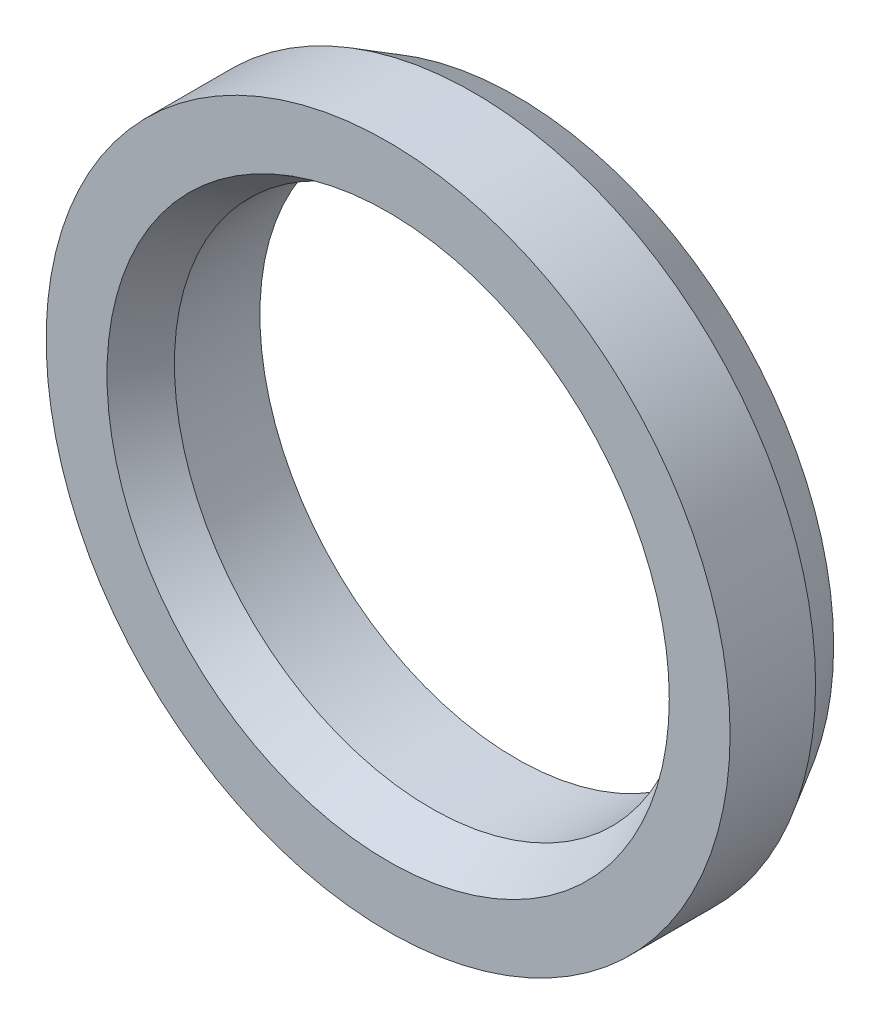
SolidWorks part; units mm, degrees
material "未指定"
ref_plane "正面" through (0, 0, 0) normal (0, 0, 1) x (1, 0, 0)
ref_plane "平面" through (0, 0, 0) normal (0, 1, 0) x (1, 0, 0)
ref_plane "右側面" through (0, 0, 0) normal (1, 0, 0) x (0, 0, -1)
sketch "ｽｹｯﾁ1" plane through (0, 0, 0) normal (1, 0, 0) x (0, 0, -1)
  line L0 (0, 0) -> (1.7825, 0) construction
  line L1 (0, 3) -> (1.5, 3)
  point P5 (0, 0)
  dimension "D1" = 1.5
  dimension "D2" = 6
revolve "回転-薄板1" add sketch "ｽｹｯﾁ1" angle 360 about L0 wall 1
chamfer "面取り1" distance 0.5 angle 30 2 edges at (4, 0, -1.5) (3, 0, 0)
